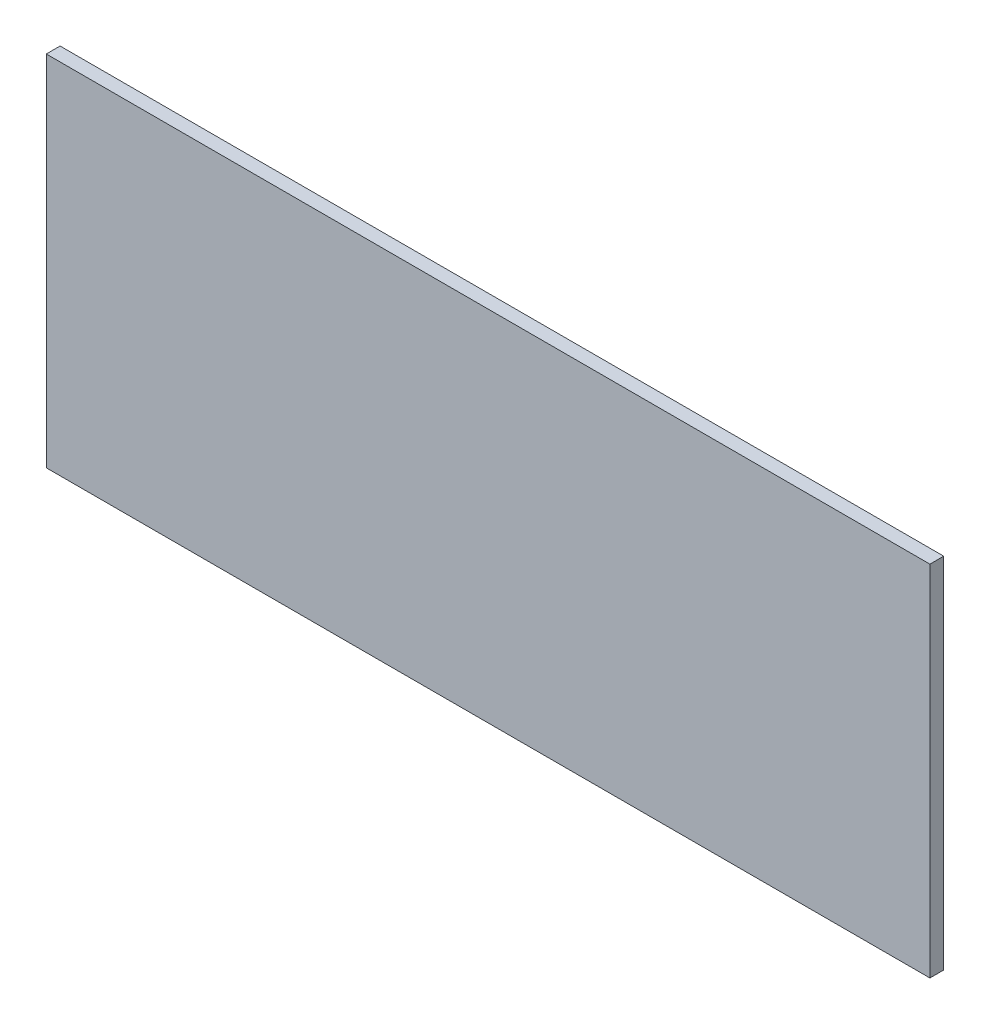
SolidWorks part; units mm, degrees
ref_plane "Alzado" through (0, 0, 0) normal (0, 0, 1) x (1, 0, 0)
ref_plane "Planta" through (0, 0, 0) normal (0, 1, 0) x (1, 0, 0)
ref_plane "Vista lateral" through (0, 0, 0) normal (1, 0, 0) x (0, 0, -1)
sketch "Croquis1" plane through (0, 0, 0) normal (0, 0, 1) x (1, 0, 0)
  line L1 (-80, 32.45) -> (80, 32.45)
  line L2 (-80, 32.45) -> (-80, -32.45)
  line L3 (-80, -32.45) -> (80, -32.45)
  line L4 (80, 32.45) -> (80, -32.45)
  line L5 (-80, 32.45) -> (80, -32.45) construction
  line L6 (-80, -32.45) -> (80, 32.45) construction
  point P0 (0, 0)
  dimension "D1" = 64.9
  dimension "D2" = 160
extrude "Saliente-Extruir1" add sketch "Croquis1" along normal blind 2.5
equation "\"D1@Croquis1\" = 65 - ( \"TOLERANCIA\" * 2 )"
equation "\"D1@Saliente-Extruir1\"= \"GROSOR_PARED_IMPRESION\""
equation "\"GROSOR_PARED_IMPRESION\"= 2.5"
equation "\"TOLERANCIA\"= 0.05"
